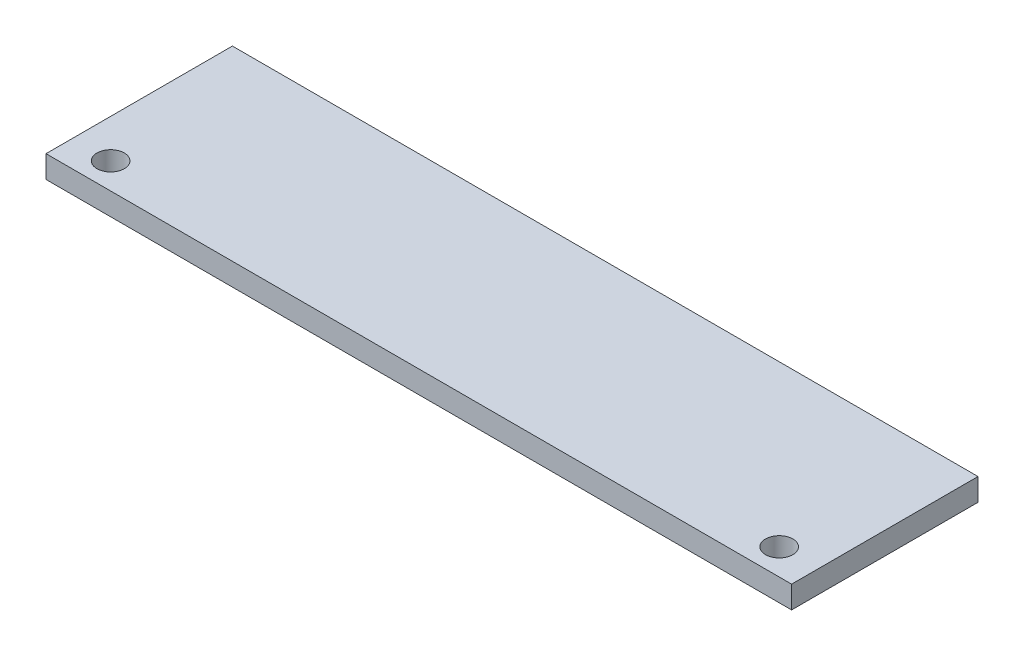
SolidWorks part; units mm, degrees
ref_plane "Plan de face" through (0, 0, 0) normal (0, 0, 1) x (1, 0, 0)
ref_plane "Plan de dessus" through (0, 0, 0) normal (0, 1, 0) x (1, 0, 0)
ref_plane "Plan de droite" through (0, 0, 0) normal (1, 0, 0) x (0, 0, -1)
sketch "Esquisse1" plane through (0, 0, 0) normal (0, 1, 0) x (1, 0, 0)
  line L1 (-300, 75) -> (300, 75)
  line L2 (-300, 75) -> (-300, -75)
  line L3 (-300, -75) -> (300, -75)
  line L4 (300, 75) -> (300, -75)
  line L5 (-300, 75) -> (300, -75) construction
  line L6 (-300, -75) -> (300, 75) construction
  point P0 (0, 0)
  dimension "D1" = 600
  dimension "D2" = 150
extrude "Boss.-Extru.1" add sketch "Esquisse1" along normal blind 18
sketch "Esquisse2" plane through (0, 18, 0) normal (0, 1, 0) x (1, 0, 0)
  line L0 (-300, 75) -> (-300, -75) construction
  line L1 (-300, 55) -> (300, 55)
  line L2 (-300, 55) -> (-300, 35)
  line L3 (-300, 35) -> (300, 35)
  line L4 (300, 55) -> (300, 35)
  line L5 (300, -75) -> (300, 75) construction
  line L6 (300, 75) -> (-300, 75) construction
  dimension "D1" = 20
  dimension "D2" = 20
sketch "Esquisse3" plane through (0, 18, 0) normal (0, 1, 0) x (1, 0, 0)
  line L0 (-238, -75) -> (-238, -33) construction
  line L1 (-300, -75) -> (300, -75) construction
  line L2 (-238, -33) -> (-300, -33) construction
  line L3 (-300, 75) -> (-300, -75) construction
  line L4 (238, -75) -> (238, -33) construction
  line L5 (238, -33) -> (300, -33) construction
  line L6 (300, -75) -> (300, 75) construction
  line L7 (238, -33) -> (300, -75) construction
  line L8 (-238, -33) -> (-300, -75) construction
  circle A0 centre (269, -54) radius 11
  circle A1 centre (-269, -54) radius 11
  dimension "D5" = 22
  dimension "D6" = 22
  dimension "D1" = 62
  dimension "D2" = 42
  dimension "D3" = 62
  dimension "D4" = 42
extrude "Enlèv. mat.-Extru.1" cut sketch "Esquisse3" against normal blind 20
